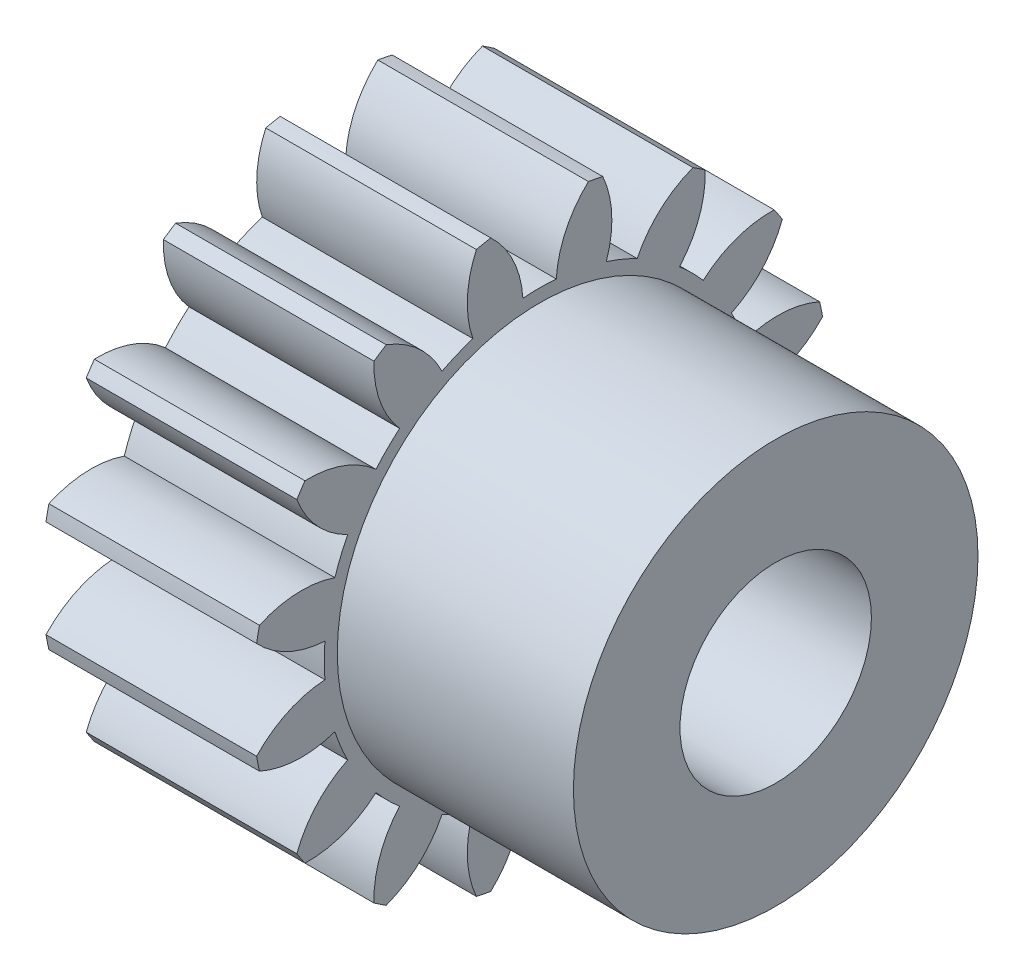
SolidWorks part; units mm, degrees
material "Laiton"
ref_plane "Plane1" through (0, 0, 0) normal (0, 0, 1) x (1, 0, 0)
ref_plane "Plane2" through (0, 0, 0) normal (0, 1, 0) x (1, 0, 0)
ref_plane "Plane3" through (0, 0, 0) normal (1, 0, 0) x (0, 0, -1)
sketch "HoldingSke" plane through (0, 0, 0) normal (0, 1, 0) x (1, 0, 0)
  line L0 (0, 0) -> (1.9225, -0.5513)
  line L1 (-15, 0) -> (100, 0) construction
  line L2 (0, 0) -> (-2.1039, 2.3779)
  line L3 (0, 0) -> (-11.863, 4.5341)
  line L4 (0, 0) -> (8.3015, 2.3804)
  line L5 (0, 0) -> (-46.8476, -17.4728)
  line L6 (0, 0) -> (-2.7356, -1.8457)
  line L7 (-2.1039, 2.3779) -> (8.6586, 51.2059)
  line L8 (-76.2, 54.61) -> (-75.7, 54.61)
  line L9 (-71.009, 38.7566) -> (-53.1078, 45.2721)
  line L10 (-76.2, 71.12) -> (104.1128, 71.12)
  line L11 (0, 0) -> (-3.3, 0)
  line L12 (-76.2, 101.6) -> (-76.181, 101.6)
  line L13 (24.9733, 27.94) -> (52.9518, 28.4284)
  line L14 (24.9733, 27.94) -> (24.9743, 27.94)
  line L15 (24.9733, 27.94) -> (100.4006, 29.5858)
  line L16 (-63.627, -0.5) -> (-12.827, -0.5)
  circle A0 centre (0, 0) radius 1.5
  circle A1 centre (0, 0) radius 3.374
  circle A2 centre (0, 0) radius 37.5
  circle A3 centre (0, 0) radius 1.5
  dimension "MHD" = 6.748
  dimension "Hub_dia" = 75
  dimension "Bore" = 3
  dimension "MBD" = 3
  dimension "Num_teeth" = 16
  dimension "Pitch" = 2
  dimension "Overall_len" = 50
  dimension "Show_teeth" = 16
  dimension "Thickness" = 3.3
  dimension "OAL" = 50.0001
  dimension "T_dim" = 0.5
  dimension "Ap" = 20
  dimension "H" = 19.05
  dimension "Pitch_radius" = 180.3128
  dimension "Width" = 3.3
  dimension "Backlash" = 0.019
  dimension "Addendum_fac" = 1
  dimension "Dedendum_fac" = 1.25
  dimension "Clearance_fac" = 0.25
  dimension "Dedendum_add" = 0.001
  dimension "Module" = 0.5
sketch "BasProSke" plane through (0, 0, 0) normal (0, 1, 0) x (1, 0, 0)
  line L0 (-10, 0) -> (60, 0) construction
  line L1 (0, 0) -> (0, 4.5)
  line L2 (0, 0) -> (3.3, 0)
  line L3 (3.3, 0) -> (3.3, 4.5)
  line L4 (3.3, 4.5) -> (0, 4.5)
  dimension "Thickness" = 3.3
  dimension "Diameter" = 9
revolve "Base-Revolve" add sketch "BasProSke" angle 360 about L0
sketch "TooCutSke" plane through (0, 0, 0) normal (1, 0, 0) x (0, 0, -1)
  line L1 (0, 0) -> (0, 107) construction
  line L2 (0, 0) -> (-0.4253, 3.9773) construction
  line L3 (0, 0) -> (-1.5544, 7.8146) construction
  line L4 (-0.4253, 3.9773) -> (-0.7772, 3.9073) construction
  arc A0 (0.2619, 3.3638) -> (-0.2619, 3.3638) centre (0, 0) ccw
  arc A1 (0.7886, 4.4562) -> (-0.7886, 4.4562) centre (0, 0) ccw
  circle A2 centre (0, 0) radius 4 construction
  circle A3 centre (0, 0) radius 3.7588 construction
  arc A4 (-0.2619, 3.3638) -> (-0.7886, 4.4562) centre (-1.8589, 3.2669) ccw
  arc A5 (0.7886, 4.4562) -> (0.2619, 3.3638) centre (1.8589, 3.2669) ccw
  dimension "Root_dia" = 6.748
  dimension "Overcut_dia" = 9.0508
  dimension "Pitch_dia" = 8
  dimension "Base_dia" = 7.5175
  dimension "Flank_rad" = 1.6
  dimension "Half_ang" = 11.25
  dimension "Half_CT" = 0.3588
extrude "ToothCut" cut sketch "TooCutSke" along normal through all
fillet "Breaks" [suppressed] radius 0.01
fillet "RootFillets" [suppressed] radius 0.126
pattern_circular "TeethCuts" count 16 every 22.5 about axis through (-10, 0, 0) along (1, 0, 0) of "ToothCut", "RootFillets", "Breaks"
sketch "HubNeaOneSke" plane through (0, 0, 0) normal (-1, 0, 0) x (0, 0, 1)
  circle A0 centre (0, 0) radius 3.374
  dimension "Diameter" = 6.748
extrude "HubNearOne" [suppressed] add sketch "HubNeaOneSke" along normal blind 46.7001
sketch "HubNeaBotSke" plane through (0, 0, 0) normal (-1, 0, 0) x (0, 0, 1)
  circle A0 centre (0, 0) radius 3.374
  dimension "Diameter" = 6.748
extrude "HubNearBoth" [suppressed] add sketch "HubNeaBotSke" along normal blind 23.35
ref_plane "FarPln" through (3.3, 0, 0) normal (1, 0, 0) x (0, 0, -1)
sketch "HubFarSke" plane through (3.3, 0, 0) normal (1, 0, 0) x (0, 0, -1)
  circle A0 centre (0, 0) radius 3.374
  dimension "Diameter" = 6.748
extrude "HubFar" [suppressed] add sketch "HubFarSke" along normal blind 23.35
sketch "BorSke" plane through (0, 0, 0) normal (1, 0, 0) x (0, 0, -1)
  circle A0 centre (0, 0) radius 1.5
  dimension "Diameter" = 3
extrude "Bore" cut sketch "BorSke" along normal mid plane 100.0001
sketch "KeySke" plane through (0, 0, 0) normal (1, 0, 0) x (0, 0, -1)
  line L0 (-0.6, 0) -> (-0.6, 2)
  line L1 (-0.6, 2) -> (0.6, 2)
  line L2 (0.6, 2) -> (0.6, 0)
  line L3 (0, 0) -> (0, 34) construction
  line L4 (-0.6, 0) -> (0.6, 0)
  dimension "Offset" = 2
  dimension "Width" = 1.2
extrude "Keyway" [suppressed] cut sketch "KeySke" along normal mid plane 100.0001
pattern_circular "Keyway2" [suppressed] count 2 every 90 about axis through (-10, 0, 0) along (1, 0, 0)
sketch "Esquisse1" plane through (3.3, 0, 0) normal (1, 0, 0) x (0, 0, -1)
  circle A0 centre (0, 0) radius 1.5
  circle A1 centre (0, 0) radius 3.17
  circle A2 centre (0, 0) radius 1.5 construction
  dimension "D1" = 6.34
extrude "Boss.-Extru.1" add sketch "Esquisse1" along normal blind 3.7
equation "' \"Module@HoldingSke\" = 6.35"
equation "' \"Num_teeth@HoldingSke\" = 12"
equation "' \"Ap@HoldingSke\" =  20"
equation "' \"Ap@HoldingSke\" = 20"
equation "' \"Width@HoldingSke\" = 0.5 * 25.4"
equation "' \"Hub_dia@HoldingSke\"= 1 * 25.4"
equation "' \"Hub_dia@HoldingSke\" = 1 * 25.4"
equation "' \"Overall_len@HoldingSke\" = 1.0 * 25.4"
equation "' \"Bore@HoldingSke\" = 0.75 * 25.4"
equation "' \"T_dim@HoldingSke\" = 0.1 * 25.4"
equation "' \"Width@KeySke\" = 0.25 * 25.4"
equation "' \"Show_teeth@HoldingSke\" = 13"
equation "' \"Backlash@HoldingSke\" = 0.009 * 25.4"
equation "' \"Addendum_fac@HoldingSke\" = 1.0"
equation "' \"Dedendum_fac@HoldingSke\" = 1.25"
equation "' \"Dedendum_add@HoldingSke\" = 0.00005 * 25.4"
equation "' \"Clearance_fac@HoldingSke\" = 0.25"
equation "\"Pitch@HoldingSke\" = 1 / \"Module@HoldingSke\""
equation "\"Overcut_dia@TooCutSke\" = (\"Num_teeth@HoldingSke\" + 2 * \"Addendum_fac@HoldingSke\") / \"Pitch@HoldingSke\" + 0.002 * 25.4"
equation "\"Pitch_dia@TooCutSke\" = \"Num_teeth@HoldingSke\" / \"Pitch@HoldingSke\""
equation "\"Base_dia@TooCutSke\" = \"Num_teeth@HoldingSke\" / \"Pitch@HoldingSke\" * cos((\"Ap@HoldingSke\"  * 3.14159265 / 180))"
equation "\"Root_dia@TooCutSke\" = (\"Num_teeth@HoldingSke\" + 2) / \"Pitch@HoldingSke\" - 2 * (\"Addendum_fac@HoldingSke\" + \"Dedendum_fac@HoldingSke\") / \"Pitch@HoldingSke\" - \"Dedendum_add@HoldingSke\" * 2"
equation "\"Half_ang@TooCutSke\" = 180 / \"Num_teeth@HoldingSke\""
equation "\"Half_CT@TooCutSke\" = \"Num_teeth@HoldingSke\" / \"Pitch@HoldingSke\" * sin((3.14159265 / 2 / \"Num_teeth@HoldingSke\")) / 2 - 7 * \"Backlash@HoldingSke\" / 4"
equation "\"Flank_rad@TooCutSke\" = \"Num_teeth@HoldingSke\" / \"Pitch@HoldingSke\" / 5"
equation "\"Radius@RootFillets\" = \"Clearance_fac@HoldingSke\" / \"Pitch@HoldingSke\" + \"Dedendum_add@HoldingSke\""
equation "\"Break_rad@Breaks\" = 0.02 / \"Pitch@HoldingSke\""
equation "\"Thickness@HoldingSke\" = \"Width@HoldingSke\""
equation "\"OAL@HoldingSke\" = \"Thickness@HoldingSke\""
equation "\"MHD@HoldingSke\" = (\"Num_teeth@HoldingSke\" + 2) / \"Pitch@HoldingSke\" - 2 * (\"Addendum_fac@HoldingSke\" + \"Dedendum_fac@HoldingSke\")  / \"Pitch@HoldingSke\" - \"Dedendum_add@HoldingSke\" * 2"
equation "\"MBD@HoldingSke\" = (\"Num_teeth@HoldingSke\" + 2) / \"Pitch@HoldingSke\" - 2 * (\"Addendum_fac@HoldingSke\" + \"Dedendum_fac@HoldingSke\")  / \"Pitch@HoldingSke\" - \"Dedendum_add@HoldingSke\" * 2 - 0.002 * 25.4"
equation "\"MHD@HoldingSke\" = ((sgn( \"MHD@HoldingSke\" - \"Hub_dia@HoldingSke\" )-1)*( \"MHD@HoldingSke\" - \"Hub_dia@HoldingSke\" ))/-2+ \"Hub_dia@HoldingSke\""
equation "\"MBD@HoldingSke\" = ((sgn( \"MBD@HoldingSke\" - \"Bore@HoldingSke\" )-1)*( \"MBD@HoldingSke\" - \"Bore@HoldingSke\" ))/-2+ \"Bore@HoldingSke\""
equation "\"OAL@HoldingSke\" = ((sgn( \"OAL@HoldingSke\" - \"Overall_len@HoldingSke\" )+1)*( \"OAL@HoldingSke\" - \"Overall_len@HoldingSke\" ))/2 + \"Overall_len@HoldingSke\" + 0.000002 * 25.4"
equation "\"Num_teeth@TeethCuts\" = int( \"Show_teeth@HoldingSke\" ) + 1"
equation "\"Num_teeth@TeethCuts\" = ((sgn( \"Num_teeth@TeethCuts\" - \"Num_teeth@HoldingSke\" )-1)*( \"Num_teeth@TeethCuts\" - \"Num_teeth@HoldingSke\" ))/-2+ \"Num_teeth@HoldingSke\""
equation "\"Num_teeth@TeethCuts\" = ((sgn( \"Num_teeth@TeethCuts\" - 2.0)+1)*( \"Num_teeth@TeethCuts\" - 2.0))/2 +2.0"
equation "\"Angle@TeethCuts\" = 360.0 / \"Num_teeth@HoldingSke\""
equation "\"Diameter@BasProSke\" = (\"Num_teeth@HoldingSke\" + 2 * \"Addendum_fac@HoldingSke\") / \"Pitch@HoldingSke\""
equation "\"Thickness@BasProSke\"  = \"Thickness@HoldingSke\""
equation "' \"Fillet_rad@BasProSke\" =  \"Thickness@HoldingSke\" * 0.05"
equation "' \"Fillet_rad@BasProSke\" = \"Thickness@HoldingSke\" * 0.05"
equation "\"MHD@HoldingSke\" = ((sgn( \"MHD@HoldingSke\" - \"Root_dia@TooCutSke\" )-1)*( \"MHD@HoldingSke\" - \"Root_dia@TooCutSke\" ))/-2+ \"Root_dia@TooCutSke\""
equation "\"Diameter@HubNeaOneSke\" = \"MHD@HoldingSke\""
equation "\"Length@HubNearOne\" = \"OAL@HoldingSke\" - \"Thickness@BasProSke\""
equation "\"Diameter@HubNeaBotSke\" = \"MHD@HoldingSke\""
equation "\"Length@HubNearBoth\" = ( \"OAL@HoldingSke\" - \"Thickness@BasProSke\" ) / 2.0"
equation "\"Thickness@FarPln\" = \"Thickness@BasProSke\""
equation "\"Diameter@HubFarSke\" = \"MHD@HoldingSke\""
equation "\"Length@HubFar\" = ( \"OAL@HoldingSke\" - \"Thickness@BasProSke\" ) / 2.0"
equation "\"Diameter@BorSke\" = \"MBD@HoldingSke\""
equation "\"D1@Bore\" = \"OAL@HoldingSke\" * 2.0"
equation "\"D1@Keyway\" = \"OAL@HoldingSke\" * 2.0"
equation "\"Offset@KeySke\" = \"T_dim@HoldingSke\" + \"MBD@HoldingSke\" / 2.0"
